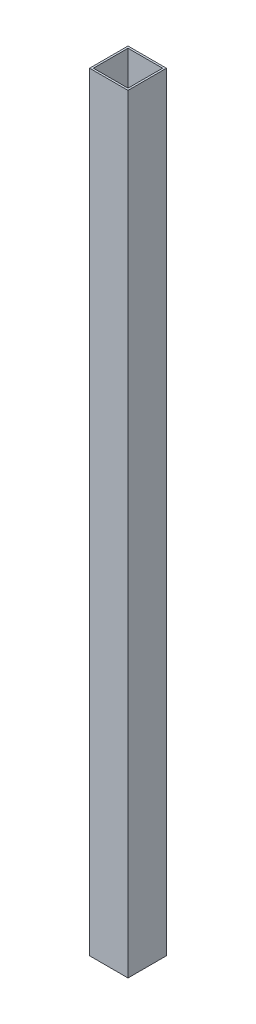
SolidWorks part; units mm, degrees
ref_plane "Plan de face" through (0, 0, 0) normal (0, 0, 1) x (1, 0, 0)
ref_plane "Plan de dessus" through (0, 0, 0) normal (0, 1, 0) x (1, 0, 0)
ref_plane "Plan de droite" through (0, 0, 0) normal (1, 0, 0) x (0, 0, -1)
sketch "Esquisse1" plane through (0, 0, 0) normal (0, 1, 0) x (1, 0, 0)
  line L0 (9, 9) -> (-9, 9)
  line L1 (10, -10) -> (-10, -10)
  line L2 (10, -10) -> (10, 10)
  line L3 (10, 10) -> (-10, 10)
  line L4 (-10, -10) -> (-10, 10)
  line L5 (10, -10) -> (-10, 10) construction
  line L6 (10, 10) -> (-10, -10) construction
  line L7 (-9, -9) -> (-9, 9)
  line L8 (9, -9) -> (-9, -9)
  line L9 (9, -9) -> (9, 9)
  point P0 (0, 0)
  dimension "D1" = 20
  dimension "D2" = 20
  dimension "D3" = 1
extrude "Boss.-Extru.1" add sketch "Esquisse1" along normal blind 400
